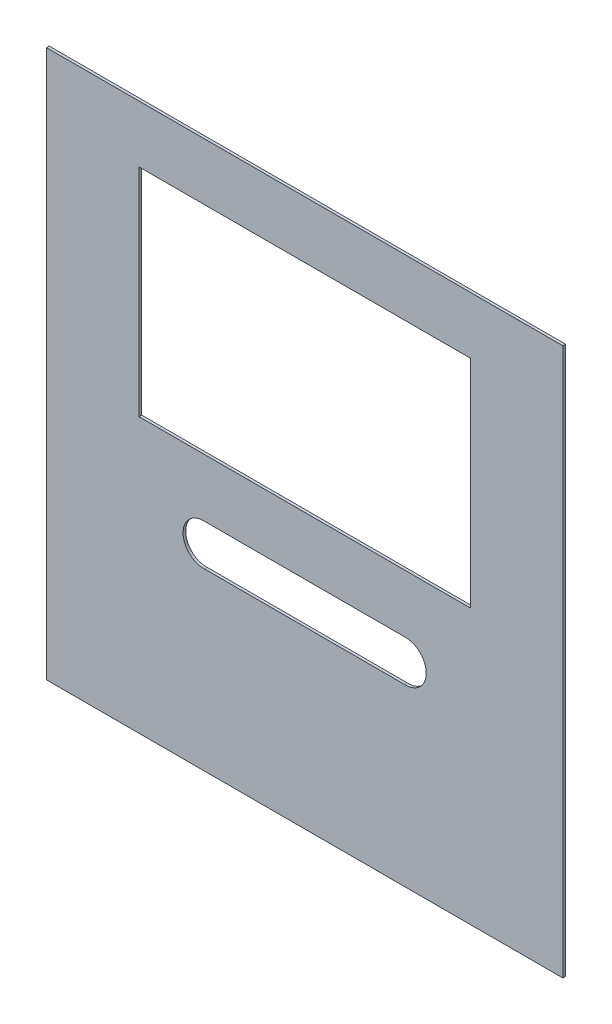
SolidWorks part; units mm, degrees
ref_plane "Front Plane" through (0, 0, 0) normal (0, 0, 1) x (1, 0, 0)
ref_plane "Top Plane" through (0, 0, 0) normal (0, 1, 0) x (1, 0, 0)
ref_plane "Right Plane" through (0, 0, 0) normal (1, 0, 0) x (0, 0, -1)
ref_plane "Plane1" through (0, 0, 0) normal (0, 0, -1) x (-1, 0, 0)
sketch "Sketch1" plane through (0, 0, 0) normal (0, 0, -1) x (-1, 0, 0)
  line L0 (191, 225) -> (-191, 225)
  line L1 (-191, 225) -> (-191, -180)
  line L2 (-191, -180) -> (191, -180)
  line L3 (191, -180) -> (191, 225)
  point P4 (0, 225)
  dimension "D1" = 382
  dimension "D2" = 405
extrude "Boss-Extrude1" add sketch "Sketch1" against normal blind 2
sketch "Sketch2" plane through (0, 0, 2) normal (0, 0, 1) x (1, 0, 0)
  line L0 (-75.5, -35.65) -> (75.4825, -35.65)
  line L1 (75.4825, -4.35) -> (-75.5, -4.35)
  arc A0 (-75.5, -4.35) -> (-75.5, -35.65) centre (-75.5, -20) ccw
  arc A1 (75.4825, -35.65) -> (75.4825, -4.35) centre (75.6555, -20) cw
extrude "Cut-Extrude1" cut sketch "Sketch2" against normal through all
sketch "Sketch3" plane through (0, 0, 0) normal (0, 0, -1) x (-1, 0, 0)
  line L0 (132.8892, 176.8145) -> (132.8892, 19.8145)
  line L1 (132.8892, 19.8145) -> (-134.1108, 19.8145)
  line L2 (-134.1108, 19.8145) -> (-134.1108, 176.8145)
  line L3 (-134.1108, 176.8145) -> (132.8892, 176.8145)
extrude "Boss-Extrude2" add sketch "Sketch3" along normal blind 15
sketch "Sketch4" plane through (0, 0, -15) normal (0, 0, -1) x (-1, 0, 0)
  line L0 (129.8892, 22.8145) -> (129.8892, 173.8145)
  line L1 (129.8892, 173.8145) -> (-131.1108, 173.8145)
  line L2 (-131.1108, 173.8145) -> (-131.1108, 22.8145)
  line L3 (-131.1108, 22.8145) -> (129.8892, 22.8145)
extrude "Cut-Extrude2" cut sketch "Sketch4" against normal blind 15
sketch "Sketch5" plane through (0, 0, 0) normal (0, 0, -1) x (-1, 0, 0)
  line L0 (-122.5, 182.8145) -> (-122.5, 22.8145)
  line L1 (-122.5, 22.8145) -> (122.5, 22.8145)
  line L2 (122.5, 22.8145) -> (122.5, 182.8145)
  line L3 (122.5, 182.8145) -> (-122.5, 182.8145)
  line L4 (0, 0) -> (0, 210.6565) construction
  line L5 (-131.1108, 22.8145) -> (129.8892, 22.8145) construction
  dimension "D1" = 245
  dimension "D2" = 160
  dimension "D3" = 122.5
extrude "Cut-Extrude3" cut sketch "Sketch5" against normal through all
ref_plane "Plane2" through (0, -20, 0) normal (0, 1, 0) x (1, 0, 0)
sketch "Sketch7" plane through (-132.8892, 0, 0) normal (-1, 0, 0) x (0, 0, 1)
  line L4 (0, 19.8145) -> (0, 176.8145)
  line L5 (0, 176.8145) -> (-15, 176.8145)
  line L6 (-15, 176.8145) -> (-15, 19.8145)
  line L7 (-15, 19.8145) -> (0, 19.8145)
  line L8 (0, 19.8145) -> (0, 176.8145)
  line L9 (0, 176.8145) -> (-15, 176.8145)
  line L10 (-15, 176.8145) -> (-15, 19.8145)
  line L11 (-15, 19.8145) -> (0, 19.8145)
  dimension "D1" = 0
extrude "Cut-Extrude4" cut sketch "Sketch7" against normal through all
sketch "Sketch9" plane through (0, 0, 0) normal (0, 0, -1) x (-1, 0, 0)
  line L0 (75.5, -35.65) -> (-75.4825, -35.65) construction
  line L1 (-75.4825, -4.35) -> (75.5, -4.35) construction
  line L2 (75.5, -35.65) -> (-75.4825, -35.65)
  line L3 (-75.4825, -4.35) -> (75.5, -4.35)
  arc A0 (75.5, -35.65) -> (75.5, -4.35) centre (75.5, -20) ccw construction
  arc A1 (-75.4825, -35.65) -> (-75.4825, -4.35) centre (-75.6555, -20) ccw construction
  arc A2 (75.5, -35.65) -> (75.5, -4.35) centre (75.5, -20) ccw
  arc A3 (-75.4825, -35.65) -> (-75.4825, -4.35) centre (-75.6555, -20) ccw
extrude "Boss-Extrude3" add sketch "Sketch9" against normal up to surface (2 mm away) up to face at (0, 102.8145, 2)
sketch "Sketch8" plane through (0, 0, 0) normal (0, 0, -1) x (-1, 0, 0)
  line L0 (0, 0) -> (0, -68.0607) construction
  line L1 (-73.8278, -20) -> (73.8278, -20)
  line L2 (-73.8278, -50.5) -> (73.8278, -50.5)
  line L3 (-191, -180) -> (191, -180) construction
  arc A2 (73.8278, -50.5) -> (73.8278, -20) centre (74.6726, -35.25) ccw
  arc A4 (-73.8278, -50.5) -> (-73.8278, -20) centre (-74.6726, -35.25) cw
  point P3 (0, -20)
  dimension "D3" = 15.2734
  dimension "D1" = 30.5
  dimension "D2" = 129.5
extrude "Cut-Extrude5" cut sketch "Sketch8" against normal through all
